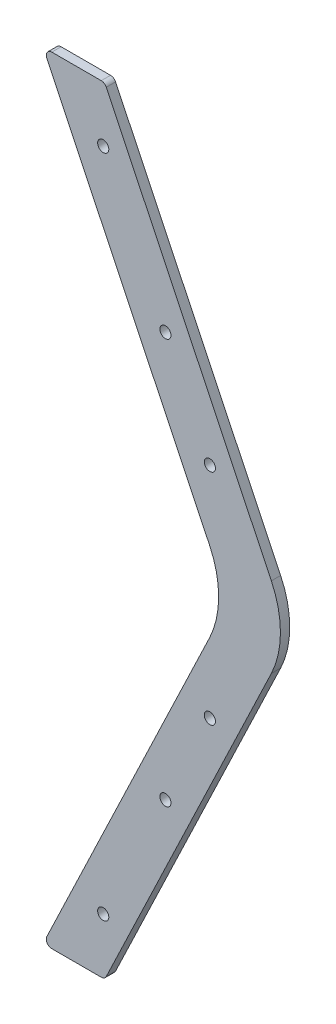
SolidWorks part; units mm, degrees
ref_plane "Ön Düzlem" through (0, 0, 0) normal (0, 0, 1) x (1, 0, 0)
ref_plane "Üst Düzlem" through (0, 0, 0) normal (0, 1, 0) x (1, 0, 0)
ref_plane "Sağ Düzlem" through (0, 0, 0) normal (1, 0, 0) x (0, 0, -1)
sketch "Çizim1" plane through (0, 0, 0) normal (0, 0, 1) x (1, 0, 0)
  line L0 (0, -209) -> (0, 209) construction
  line L1 (0, 209) -> (100, 0)
  line L2 (100, 0) -> (0, -209)
  line L3 (0, 0) -> (100, 0) construction
  line L4 (33.2572, 209) -> (133.2572, 0)
  line L5 (133.2572, 0) -> (33.2572, -209)
  line L6 (0, 209) -> (33.2572, 209)
  line L7 (0, -209) -> (33.2572, -209)
  line L8 (133.2572, 0) -> (27.0618, -221.9482) construction
  line L9 (27.0618, 221.9482) -> (133.2572, 0) construction
  point P4 (0, 0)
  dimension "D1" = 418
  dimension "D2" = 100
  dimension "D3" = 30
extrude "Yükseklik-Ekstrüzyon1" add sketch "Çizim1" along normal blind 5
fillet "Radyus1" radius 3 4 edges at (0, -209, 2.5) (0, 209, 2.5) (33.2572, 209, 2.5) (33.2572, -209, 2.5)
fillet "Radyus2" radius 50 2 edges at (133.2572, 0, 2.5) (100, 0, 2.5)
sketch "Çizim2" plane through (0, 0, 5) normal (0, 0, 1) x (1, 0, 0)
  line L0 (18.064, 209) -> (118.064, 0) construction
  line L1 (31.3669, 209) -> (4.7611, 209) construction
  line L2 (2.0549, 204.7052) -> (89.6744, 21.5804) construction
  line L3 (18.064, -209) -> (118.064, 0) construction
  line L4 (4.7611, -209) -> (31.3669, -209) construction
  line L5 (34.073, -207.2948) -> (122.9316, -21.5804) construction
  circle A0 centre (32.4181, 179) radius 3
  circle A1 centre (65.9109, 109) radius 3
  circle A2 centre (89.8343, 59) radius 3
  circle A3 centre (89.8343, -59) radius 3
  circle A4 centre (65.9109, -109) radius 3
  circle A5 centre (32.4181, -179) radius 3
  point P18 (29.9137, -184.2341)
  point P25 (60.8436, -119.5907)
  point P31 (86.0046, -67.0041)
  point P32 (86.0046, 67.0041)
  point P33 (59.848, 121.6714)
  point P34 (29.9137, 184.2341)
  dimension "D1" = 6
  dimension "D5" = 30
  dimension "D6" = 100
  dimension "D7" = 150
  dimension "D2" = 30
  dimension "D3" = 100
  dimension "D4" = 150
extrude "Kes-Ekstrüzyon1" cut sketch "Çizim2" against normal blind 10
